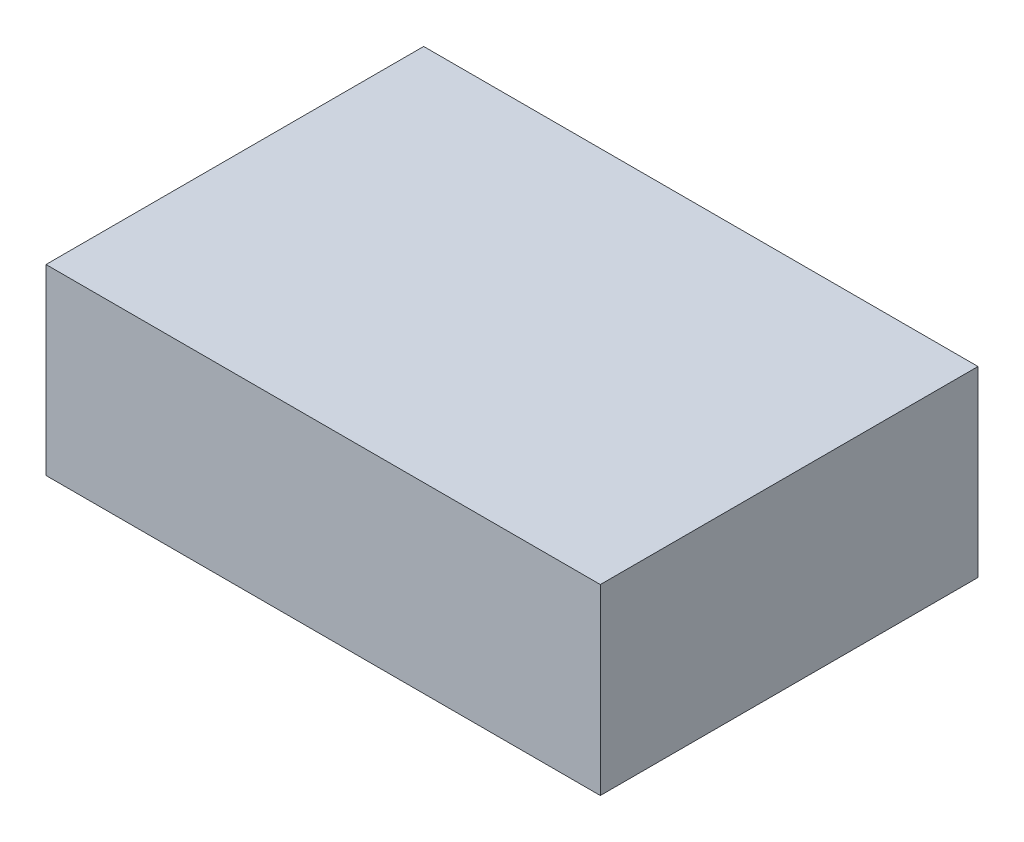
SolidWorks part; units mm, degrees
ref_plane "Front Plane" through (0, 0, 0) normal (0, 0, 1) x (1, 0, 0)
ref_plane "Top Plane" through (0, 0, 0) normal (0, 1, 0) x (1, 0, 0)
ref_plane "Right Plane" through (0, 0, 0) normal (1, 0, 0) x (0, 0, -1)
sketch "Sketch1" plane through (0, 0, 0) normal (0, 1, 0) x (1, 0, 0)
  line L1 (0, 0) -> (91, 0)
  line L2 (0, 0) -> (0, 62)
  line L3 (0, 62) -> (91, 62)
  line L4 (91, 0) -> (91, 62)
  dimension "D1" = 91
  dimension "D2" = 62
extrude "Boss-Extrude1" add sketch "Sketch1" along normal blind 30
sketch "USB, Ethernet Ports (Ass)" plane through (91, 0, 0) normal (1, 0, 0) x (0, 0, -1)
  line L9 (3.5, 25) -> (3.5, 10)
  line L10 (23.5, 25) -> (38.5, 25)
  line L11 (23.5, 25) -> (23.5, 18)
  line L12 (23.5, 18) -> (38.5, 18)
  line L13 (38.5, 25) -> (38.5, 18)
  line L14 (23.5, 13) -> (38.5, 13)
  line L15 (23.5, 13) -> (23.5, 6)
  line L16 (23.5, 6) -> (38.5, 6)
  line L17 (38.5, 13) -> (38.5, 6)
  line L18 (43.5, 25) -> (58.5, 25)
  line L19 (43.5, 25) -> (43.5, 18)
  line L20 (43.5, 18) -> (58.5, 18)
  line L21 (58.5, 25) -> (58.5, 18)
  line L22 (43.5, 13) -> (58.5, 13)
  line L23 (43.5, 13) -> (43.5, 6)
  line L24 (43.5, 6) -> (58.5, 6)
  line L25 (58.5, 13) -> (58.5, 6)
  line L26 (3.5, 10) -> (8, 10)
  line L27 (8, 10) -> (8, 8)
  line L28 (8, 8) -> (14, 8)
  line L29 (14, 8) -> (14, 10)
  line L30 (14, 10) -> (18.5, 10)
  line L31 (18.5, 10) -> (18.5, 25)
  line L32 (18.5, 25) -> (3.5, 25)
  line L33 (0, 30) -> (62, 30) construction
  point P26 (31, 30)
  point P27 (31, 25)
  dimension "D1" = 15
  dimension "D2" = 5
  dimension "D3" = 5
  dimension "D4" = 7
  dimension "D5" = 5
  dimension "D6" = 5
  dimension "D7" = 15
  dimension "D8" = 2
  dimension "D9" = 6
sketch "USB C, HDMI Ports (Ass)" plane through (0, 0, 0) normal (0, 0, 1) x (1, 0, 0)
  line L0 (5, 9) -> (18, 9) construction
  line L1 (5, 11.5) -> (18, 11.5)
  line L2 (5, 6.5) -> (18, 6.5)
  line L3 (28, 9) -> (41, 9) construction
  line L4 (28, 11.5) -> (41, 11.5)
  line L5 (28, 6.5) -> (41, 6.5)
  line L6 (51, 9) -> (64, 9) construction
  line L7 (51, 11.5) -> (64, 11.5)
  line L8 (51, 6.5) -> (64, 6.5)
  line L9 (0, 30) -> (0, 0) construction
  line L10 (0, 0) -> (91, 0) construction
  arc A0 (5, 11.5) -> (5, 6.5) centre (5, 9) ccw
  arc A1 (18, 6.5) -> (18, 11.5) centre (18, 9) ccw
  arc A2 (28, 11.5) -> (28, 6.5) centre (28, 9) ccw
  arc A3 (41, 6.5) -> (41, 11.5) centre (41, 9) ccw
  arc A4 (51, 11.5) -> (51, 6.5) centre (51, 9) ccw
  arc A5 (64, 6.5) -> (64, 11.5) centre (64, 9) ccw
  point P2 (11.5, 9)
  point P7 (34.5, 9)
  point P14 (57.5, 9)
  point P23 (30.7387, 9.8429)
  dimension "D1" = 5
  dimension "D2" = 13
  dimension "D3" = 10
  dimension "D4" = 10
  dimension "D5" = 5
  dimension "D6" = 9
